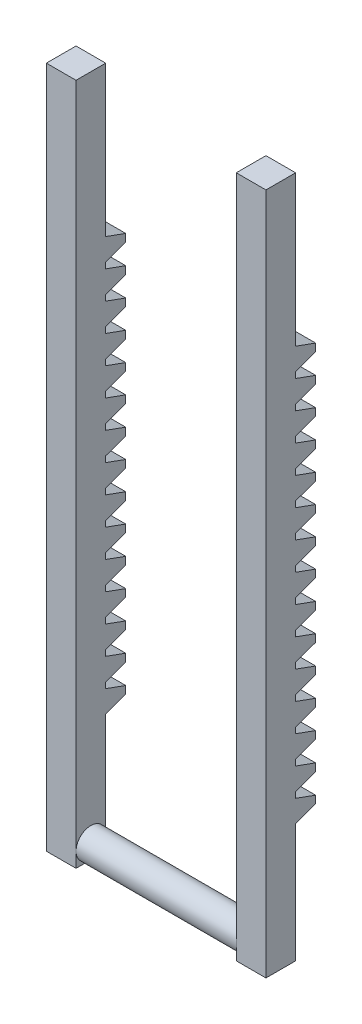
SolidWorks part; units mm, degrees
ref_plane "正面" through (0, 0, 0) normal (0, 0, 1) x (1, 0, 0)
ref_plane "平面" through (0, 0, 0) normal (0, 1, 0) x (1, 0, 0)
ref_plane "右側面" through (0, 0, 0) normal (1, 0, 0) x (0, 0, -1)
sketch "ｽｹｯﾁ1" plane through (0, 0, 0) normal (0, 1, 0) x (1, 0, 0)
  line L1 (-20.5357, 0) -> (-15.5357, 0)
  line L2 (-20.5357, 0) -> (-20.5357, 5)
  line L3 (-20.5357, 5) -> (-15.5357, 5)
  line L4 (-15.5357, 0) -> (-15.5357, 5)
  line L5 (11.4643, 0) -> (16.4643, 0)
  line L6 (11.4643, 0) -> (11.4643, 5)
  line L7 (11.4643, 5) -> (16.4643, 5)
  line L8 (16.4643, 0) -> (16.4643, 5)
  dimension "D1" = 5
  dimension "D2" = 5
  dimension "D3" = 5
  dimension "D4" = 5
  dimension "D5" = 27
extrude "ﾎﾞｽ - 押し出し2" add sketch "ｽｹｯﾁ1" against normal blind 115
sketch "ｽｹｯﾁ2" plane through (-15.5357, 0, 0) normal (1, 0, 0) x (0, 0, -1)
  line L3 (5, -115) -> (5, 0) construction
  line L4 (0, -115) -> (5, -115) construction
  circle A0 centre (2.5, -112.5) radius 2.5
  dimension "D1" = 5
  dimension "D2" = 2.5
  dimension "D3" = 2.5
extrude "ﾎﾞｽ - 押し出し3" add sketch "ｽｹｯﾁ2" along normal blind 27
sketch "ｽｹｯﾁ3" plane through (16.4643, 0, 0) normal (1, 0, 0) x (0, 0, -1)
  line L0 (5, -91.2789) -> (8.375, -92.5073)
  line L1 (5, -115) -> (5, 0) construction
  line L2 (8.375, -92.5073) -> (8.375, -93.7716)
  line L3 (8.375, -93.7716) -> (5, -95)
  line L4 (6.875, -91.9614) -> (6.875, -94.3176)
  line L5 (8.375, -93.1395) -> (5, -93.1395)
  line L6 (5, -91.2789) -> (5, -95)
  dimension "D1" = 3.375
  dimension "D2" = 1.5
  dimension "D3" = 2.3562
  dimension "D4" = 20
  dimension "D5" = 20
extrude "ﾎﾞｽ - 押し出し5" add sketch "ｽｹｯﾁ3" against normal blind 5 contours L0 L2 L3 L6
pattern_linear "直線ﾊﾟﾀｰﾝ1" count 15 spacing 4.7124 along (0, 1, 0) of "ﾎﾞｽ - 押し出し5"
sketch "ｽｹｯﾁ4" plane through (-20.5357, 0, 0) normal (-1, 0, 0) x (0, 0, 1)
  line L0 (-5, -25.3055) -> (-8.375, -26.5339)
  line L1 (-8.375, -26.5339) -> (-8.375, -27.7982)
  line L2 (-8.375, -27.7982) -> (-5, -29.0266)
  line L3 (-5, -115) -> (-5, 0) construction
  line L4 (-8.375, -27.7982) -> (-5, -29.0266) construction
  line L5 (-5, -29.0266) -> (-5, -25.3055)
extrude "ﾎﾞｽ - 押し出し6" add sketch "ｽｹｯﾁ4" against normal blind 5
pattern_linear "直線ﾊﾟﾀｰﾝ2" count 15 spacing 4.712 along (0, -1, 0) of "ﾎﾞｽ - 押し出し6"
equation "\"モジュール\"= 1.5"
equation "\"ピッチ\"= pi * \"モジュール\""
equation "\"圧力角\"= 20"
equation "\"D1@ｽｹｯﾁ3\"=\"モジュール\"*2.25"
equation "\"D2@ｽｹｯﾁ3\"=\"モジュール\"*1"
equation "\"D3@ｽｹｯﾁ3\"=\"ピッチ\"/2"
equation "\"D4@ｽｹｯﾁ3\"=\"圧力角\""
equation "\"D3@直線ﾊﾟﾀｰﾝ1\"=\"ピッチ\""
